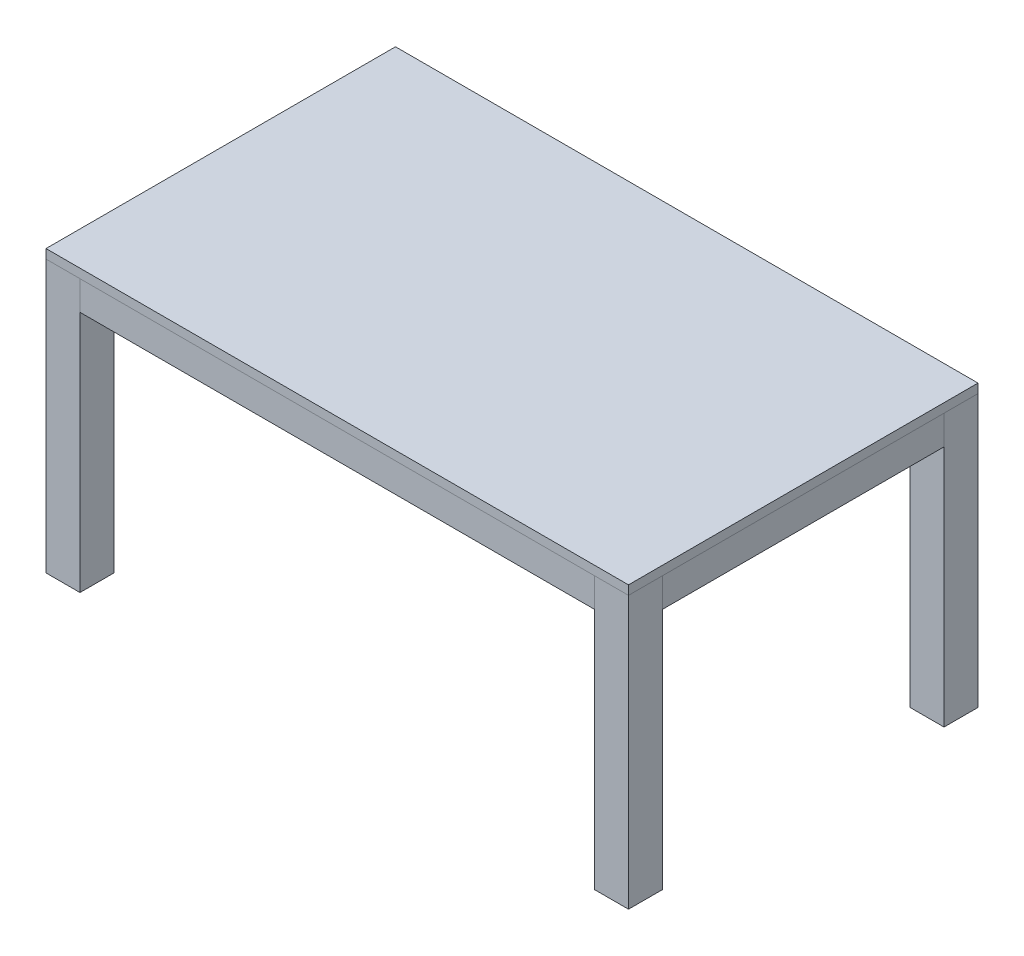
SolidWorks part; units mm, degrees
ref_plane "Front Plane" through (0, 0, 0) normal (0, 0, 1) x (1, 0, 0)
ref_plane "Top Plane" through (0, 0, 0) normal (0, 1, 0) x (1, 0, 0)
ref_plane "Right Plane" through (0, 0, 0) normal (1, 0, 0) x (0, 0, -1)
sketch "Sketch1" plane through (0, 0, 0) normal (0, 1, 0) x (1, 0, 0)
  line L1 (-717.55, -412.75) -> (717.55, -412.75) construction
  line L2 (-717.55, -412.75) -> (-717.55, 412.75) construction
  line L3 (-717.55, 412.75) -> (717.55, 412.75) construction
  line L4 (717.55, -412.75) -> (717.55, 412.75) construction
  line L5 (-717.55, -412.75) -> (717.55, 412.75) construction
  line L6 (-717.55, 412.75) -> (717.55, -412.75) construction
  line L7 (-762, 457.2) -> (-673.1, 457.2)
  line L8 (-762, 457.2) -> (-762, 368.3)
  line L9 (-762, 368.3) -> (-673.1, 368.3)
  line L10 (-673.1, 457.2) -> (-673.1, 368.3)
  line L11 (-762, 457.2) -> (-673.1, 368.3) construction
  line L12 (-762, 368.3) -> (-673.1, 457.2) construction
  line L13 (673.1, 457.2) -> (762, 457.2)
  line L14 (673.1, 457.2) -> (673.1, 368.3)
  line L15 (673.1, 368.3) -> (762, 368.3)
  line L16 (762, 457.2) -> (762, 368.3)
  line L17 (673.1, 457.2) -> (762, 368.3) construction
  line L18 (673.1, 368.3) -> (762, 457.2) construction
  line L19 (673.1, -368.3) -> (762, -368.3)
  line L20 (673.1, -368.3) -> (673.1, -457.2)
  line L21 (673.1, -457.2) -> (762, -457.2)
  line L22 (762, -368.3) -> (762, -457.2)
  line L23 (673.1, -368.3) -> (762, -457.2) construction
  line L24 (673.1, -457.2) -> (762, -368.3) construction
  line L25 (-762, -368.3) -> (-673.1, -368.3)
  line L26 (-762, -368.3) -> (-762, -457.2)
  line L27 (-762, -457.2) -> (-673.1, -457.2)
  line L28 (-673.1, -368.3) -> (-673.1, -457.2)
  line L29 (-762, -368.3) -> (-673.1, -457.2) construction
  line L30 (-762, -457.2) -> (-673.1, -368.3) construction
  point P0 (0, 0)
  dimension "D1" = 88.9
  dimension "D2" = 1524
  dimension "D3" = 914.4
extrude "Boss-Extrude1" add sketch "Sketch1" along normal blind 711.2
sketch "Sketch2" plane through (0, 711.2, 0) normal (0, 1, 0) x (1, 0, 0)
  line L1 (-762, 457.2) -> (762, 457.2)
  line L2 (-762, 457.2) -> (-762, -457.2)
  line L3 (-762, -457.2) -> (762, -457.2)
  line L4 (762, 457.2) -> (762, -457.2)
extrude "Boss-Extrude2" add sketch "Sketch2" along normal blind 23.8125 separate body
sketch "Sketch3" plane through (0, 0, -368.3) normal (0, 0, 1) x (1, 0, 0)
  line L0 (0, 0) -> (0, 50000) construction
  line L1 (-762, 711.2) -> (-742.95, 711.2)
  line L2 (-762, 711.2) -> (-762, 635)
  line L3 (-762, 635) -> (-742.95, 635)
  line L4 (-742.95, 711.2) -> (-742.95, 635)
  line L5 (762, 635) -> (742.95, 635)
  line L6 (742.95, 711.2) -> (742.95, 635)
  line L7 (762, 711.2) -> (742.95, 711.2)
  line L8 (762, 711.2) -> (762, 635)
  dimension "D1" = 76.2
  dimension "D2" = 19.05
extrude "Boss-Extrude3" add sketch "Sketch3" along normal up to surface (736.6 mm away) separate body up to face at (-717.55, 355.6, 368.3)
sketch "Sketch4" plane through (-673.1, 0, 0) normal (1, 0, 0) x (0, 0, -1)
  line L0 (-368.3, 635) -> (-368.3, 711.2) construction
  line L1 (-457.2, 711.2) -> (-438.15, 711.2)
  line L2 (-457.2, 711.2) -> (-457.2, 635)
  line L3 (-457.2, 635) -> (-438.15, 635)
  line L4 (-438.15, 711.2) -> (-438.15, 635)
  line L5 (0, 0) -> (0, 50000) construction
  line L6 (457.2, 635) -> (438.15, 635)
  line L7 (438.15, 711.2) -> (438.15, 635)
  line L8 (457.2, 711.2) -> (438.15, 711.2)
  line L9 (457.2, 711.2) -> (457.2, 635)
  dimension "D1" = 19.05
extrude "Boss-Extrude4" add sketch "Sketch4" along normal up to surface (1346.2 mm away) separate body up to face at (673.1, 355.6, -412.75)
sketch "Sketch6" plane through (0, 0, 0) normal (0, -1, 0) x (1, 0, 0)
  line L0 (-673.1, 368.3) -> (-762, 368.3) construction
  line L1 (717.55, -412.75) -> (-717.55, -412.75) construction
  line L2 (717.55, -412.75) -> (717.55, 412.75) construction
  line L3 (717.55, 412.75) -> (-717.55, 412.75) construction
  line L4 (-717.55, -412.75) -> (-717.55, 412.75) construction
  line L5 (717.55, -412.75) -> (-717.55, 412.75) construction
  line L6 (717.55, 412.75) -> (-717.55, -412.75) construction
  line L7 (-673.1, 457.2) -> (-673.1, 368.3) construction
  circle A0 centre (-717.55, 412.75) radius 6.985
  circle A1 centre (-717.55, -412.75) radius 6.985
  circle A2 centre (717.55, -412.75) radius 6.985
  circle A3 centre (717.55, 412.75) radius 6.985
  point P0 (0, 0)
  point P6 (-717.55, 368.3)
  point P7 (-673.1, 412.75)
  dimension "D1" = 13.97
extrude "Cut-Extrude1" cut sketch "Sketch6" against normal blind 76.2 contours A0
